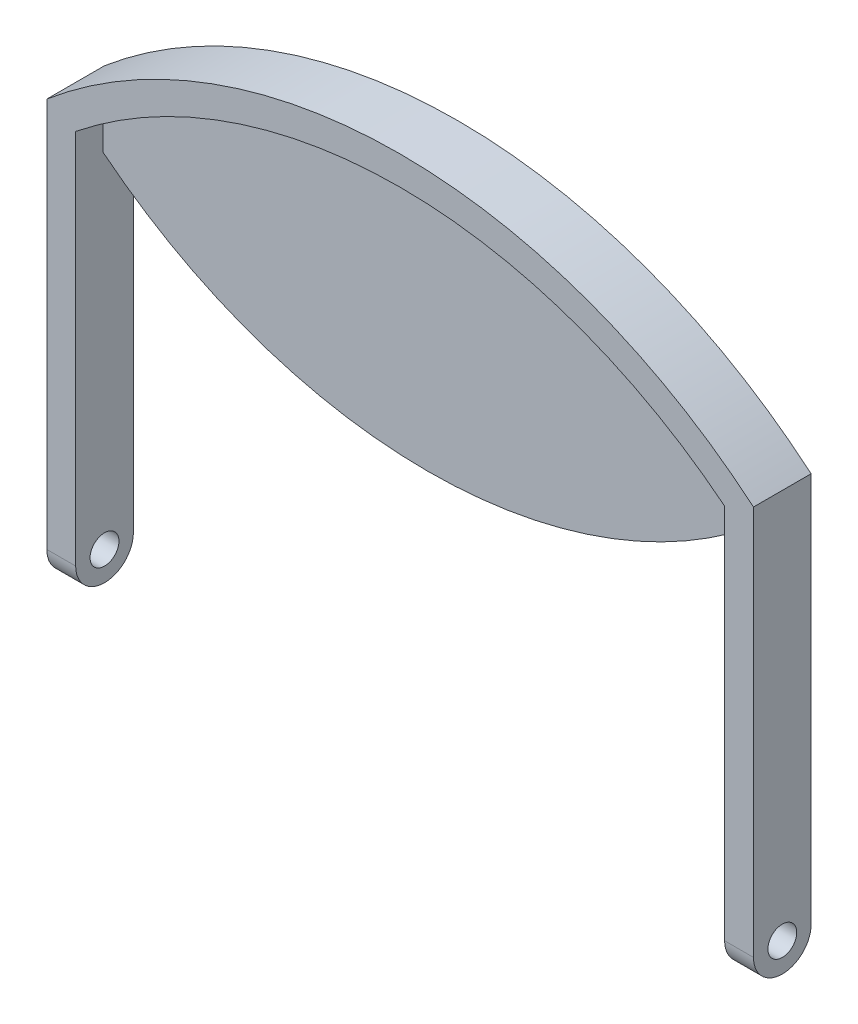
SolidWorks part; units mm, degrees
ref_plane "前视基准面" through (0, 0, 0) normal (0, 0, 1) x (1, 0, 0)
ref_plane "上视基准面" through (0, 0, 0) normal (0, 1, 0) x (1, 0, 0)
ref_plane "右视基准面" through (0, 0, 0) normal (1, 0, 0) x (0, 0, -1)
sketch "草图1" plane through (0, 0, 0) normal (0, 0, 1) x (1, 0, 0)
  line L0 (-225, 0) -> (225, 0) construction
  line L1 (-330, 0) -> (330, 0) construction
  line L2 (-225, 0) -> (-225, 281.0249) construction
  line L3 (225, 0) -> (225, 281.0249) construction
  line L4 (350, 0) -> (-350, 0) construction
  line L5 (245, 0) -> (245, 290.4738)
  line L6 (-245, 0) -> (-245, 290.4738)
  line L7 (-277.6653, 270) -> (276.9694, 270) construction
  line L8 (225, 0) -> (245, 0)
  line L9 (-245, 0) -> (-225, 0)
  line L10 (-225, 258.9751) -> (-225, 0)
  line L11 (225, 258.9751) -> (225, 0)
  arc A0 (-225, 281.0249) -> (225, 281.0249) centre (0, 0) cw construction
  arc A1 (-245, 290.4738) -> (245, 290.4738) centre (0, 0) cw
  arc A2 (-225, 258.9751) -> (225, 258.9751) centre (0, 540) ccw
  point P3 (0, 0)
  point P6 (0, 0)
  point P13 (0, 0)
  dimension "D6" = 380
  dimension "D7" = 360
  dimension "D1" = 450
  dimension "D2" = 660
  dimension "D3" = 700
  dimension "D4" = 20
  dimension "D5" = 20
  dimension "D8" = 270
extrude "凸台-拉伸1" add sketch "草图1" along normal blind 40
sketch "草图2" plane through (0, 0, 0) normal (0, 0, -1) x (-1, 0, 0)
  line L0 (225, 0) -> (225, 281.0249) construction
  line L1 (-225, 0) -> (-225, 281.0249) construction
  line L2 (225, 258.9751) -> (225, 281.0249)
  line L3 (-225, 258.9751) -> (-225, 281.0249)
  arc A0 (-225, 258.9751) -> (225, 258.9751) centre (0, 540) ccw construction
  arc A1 (225, 281.0249) -> (-225, 281.0249) centre (0, 0) ccw construction
  arc A2 (-225, 258.9751) -> (225, 258.9751) centre (0, 540) ccw
  arc A3 (225, 281.0249) -> (-225, 281.0249) centre (0, 0) ccw
extrude "切除-拉伸1" cut sketch "草图2" against normal blind 19
sketch "草图3" plane through (0, 0, 40) normal (0, 0, 1) x (1, 0, 0)
  line L0 (225, 0) -> (225, 281.0249) construction
  line L1 (-225, 0) -> (-225, 281.0249) construction
  line L2 (225, 258.9751) -> (225, 281.0249)
  line L3 (-225, 258.9751) -> (-225, 281.0249)
  arc A0 (-225, 258.9751) -> (225, 258.9751) centre (0, 540) ccw construction
  arc A1 (225, 281.0249) -> (-225, 281.0249) centre (0, 0) ccw construction
  arc A2 (-225, 258.9751) -> (225, 258.9751) centre (0, 540) ccw
  arc A3 (225, 281.0249) -> (-225, 281.0249) centre (0, 0) ccw
extrude "切除-拉伸2" cut sketch "草图3" against normal blind 19
sketch "草图4" plane through (245, 0, 0) normal (1, 0, 0) x (0, 0, -1)
  line L0 (0, 0) -> (0, 290.4738) construction
  line L1 (-40, 0) -> (0, 0) construction
  line L2 (-40, 20) -> (-40, 0)
  line L3 (-40, 0) -> (-20, 0)
  line L4 (0, 20) -> (0, 0)
  line L5 (0, 0) -> (-20, 0)
  arc A0 (-40, 20) -> (0, 20) centre (-20, 20) ccw
  line M6 (0, 0) -> (0, 290.4738)
  line M8 (-40, 290.4738) -> (-40, 0)
  line M9 (-40, 0) -> (0, 0)
  dimension "D1" = 40
  dimension "D2" = 20
  dimension "D3" = 20
extrude "切除-拉伸3" cut sketch "草图4" against normal through all contours A0 M8 M9 | A0 M9 M6
sketch "草图5" plane through (-245, 0, 0) normal (-1, 0, 0) x (0, 0, 1)
  arc A0 (0, 20) -> (40, 20) centre (20, 20) ccw construction
  arc A1 (0, 20) -> (40, 20) centre (20, 20) ccw construction
  circle A2 centre (20, 20) radius 10.007
extrude "切除-拉伸4" cut sketch "草图5" against normal through all both and the other way through all
